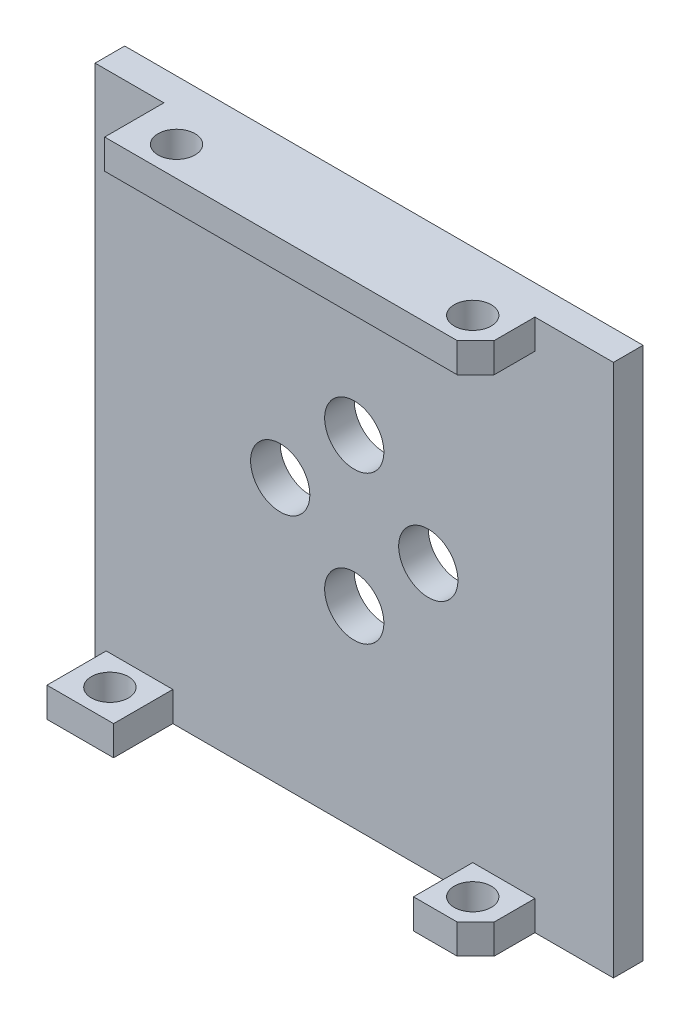
SolidWorks part; units mm, degrees
ref_plane "Alzado" through (0, 0, 0) normal (1, 0, 0) x (0, 1, 0)
ref_plane "Planta" through (0, 0, 0) normal (0, 0, 1) x (0, 1, 0)
ref_plane "Vista lateral" through (0, 0, 0) normal (0, 1, 0) x (-1, 0, 0)
sketch "Croquis1" plane through (0, 0, 0) normal (0, 0, 1) x (0, 1, 0)
  line L1 (-18, 17.5) -> (18, 17.5)
  line L2 (-18, 17.5) -> (-18, -17.5)
  line L3 (-18, -17.5) -> (18, -17.5)
  line L4 (18, 17.5) -> (18, -17.5)
  circle A0 centre (0, 5) radius 2
  circle A1 centre (5, 0) radius 2
  circle A2 centre (0, -5) radius 2
  circle A3 centre (-5, 0) radius 2
  point P16 (0, 0)
  dimension "D5" = 4
  dimension "D1" = 36
  dimension "D2" = 18
  dimension "D3" = 35
  dimension "D4" = 17.5
  dimension "D6" = 5
  dimension "D7" = 4
extrude "Saliente-Extruir1" add sketch "Croquis1" along normal blind 2
sketch "Croquis2" plane through (0, 18, 0) normal (0, 1, 0) x (-1, 0, 0)
  line L0 (-17.5, 0) -> (17.5, 0) construction
  line L1 (-10.95, 6) -> (12.8535, 6)
  line L2 (-12.2, 4.75) -> (-12.2, 0)
  line L3 (-12.2, 0) -> (12.8535, 0)
  line L4 (12.8535, 6) -> (12.8535, 0)
  line L5 (0, 0) -> (0, 6.1928) construction
  line L6 (-12.2, 4.75) -> (-10.95, 6)
  line L7 (-17.5, 2) -> (17.5, 2) construction
  circle A0 centre (-10, 4) radius 1.25
  circle A1 centre (10, 4) radius 1.25
  point P0 (-12.2, 6)
  dimension "D2" = 2.5
  dimension "D1" = 6
  dimension "D3" = 10
  dimension "D4" = 2.2
  dimension "D5" = 2
extrude "Saliente-Extruir2" add sketch "Croquis2" against normal blind 2
sketch "Croquis3" plane through (0, -18, 0) normal (0, -1, 0) x (1, 0, 0)
  line L0 (-17.5, 2) -> (17.5, 2) construction
  line L1 (-17.5, 0) -> (17.5, 0) construction
  line L2 (-16.75, 0) -> (-12.25, 0)
  line L3 (-16.75, 0) -> (-16.75, 6)
  line L4 (-16.75, 6) -> (-12.25, 6)
  line L5 (-12.25, 0) -> (-12.25, 6)
  line L6 (-12.8535, 6) -> (10.95, 6) construction
  line L7 (12.2, 4.75) -> (10.95, 6)
  line L8 (12.2, 2) -> (8, 2)
  line L9 (12.2, 2) -> (12.2, 4.75)
  line L10 (10.95, 6) -> (8, 6)
  line L11 (8, 2) -> (8, 6)
  circle A0 centre (10, 4) radius 1.25
  circle A1 centre (-14.5, 4) radius 1.2514
  point P17 (12.2, 6)
  dimension "D1" = 2.5
  dimension "D3" = 2.5028
  dimension "D2" = 2
  dimension "D4" = 24.5
  dimension "D5" = 2.25
  dimension "D6" = 4.5
  dimension "D7" = 2
  dimension "D8" = 2
extrude "Saliente-Extruir3" add sketch "Croquis3" against normal blind 2
